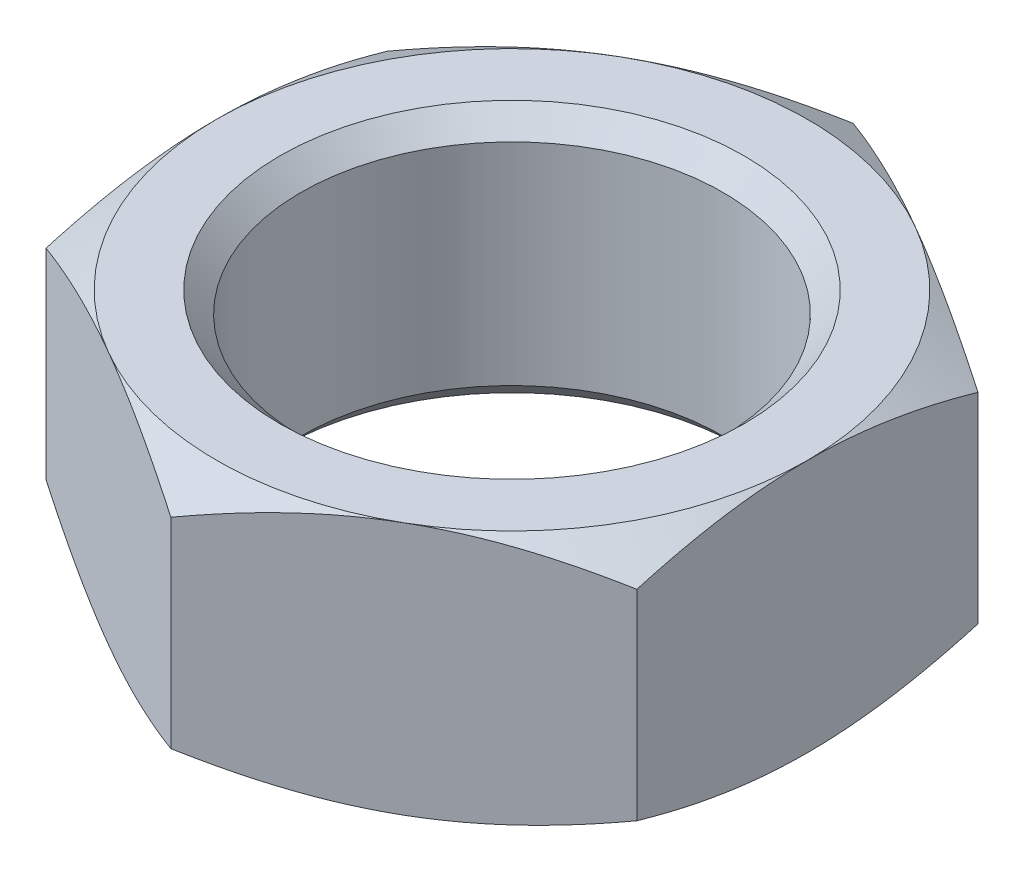
SolidWorks part; units mm, degrees
ref_plane "Front Plane" through (0, 0, 0) normal (0, 0, 1) x (1, 0, 0)
ref_plane "Top Plane" through (0, 0, 0) normal (0, 1, 0) x (1, 0, 0)
ref_plane "Right Plane" through (0, 0, 0) normal (1, 0, 0) x (0, 0, -1)
sketch "Sketch2" plane through (0, 0, 0) normal (0, 1, 0) x (1, 0, 0)
  line L1 (0, 16.1658) -> (-14, 8.0829)
  line L2 (-14, 8.0829) -> (-14, -8.0829)
  line L3 (-14, -8.0829) -> (0, -16.1658)
  line L4 (0, -16.1658) -> (14, -8.0829)
  line L5 (14, -8.0829) -> (14, 8.0829)
  line L6 (14, 8.0829) -> (0, 16.1658)
  circle A0 centre (0, 0) radius 14 construction
  dimension "D1" = 28
extrude "Boss-Extrude1" add sketch "Sketch2" along normal mid plane 12
sketch "Sketch3" plane through (0, 6, 0) normal (0, 1, 0) x (1, 0, 0)
  line L0 (14, 8.0829) -> (0, 16.1658) construction
  circle A0 centre (0, 0) radius 14
extrude "Cut-Extrude1" cut sketch "Sketch3" against normal blind 12 draft 60 flip side to cut contours A0
mirror "Mirror1" about plane through (0, 0, 0) normal (0, 1, 0) of "Cut-Extrude1"
sketch "Sketch4" plane through (0, -6, 0) normal (0, -1, 0) x (1, 0, 0)
  circle A0 centre (0, 0) radius 10
  dimension "D1" = 20
extrude "Cut-Extrude2" cut sketch "Sketch4" against normal through all
chamfer "Chamfer1" distance 1 angle 45 2 edges at (0, -6, -10) (0, 6, -10)
